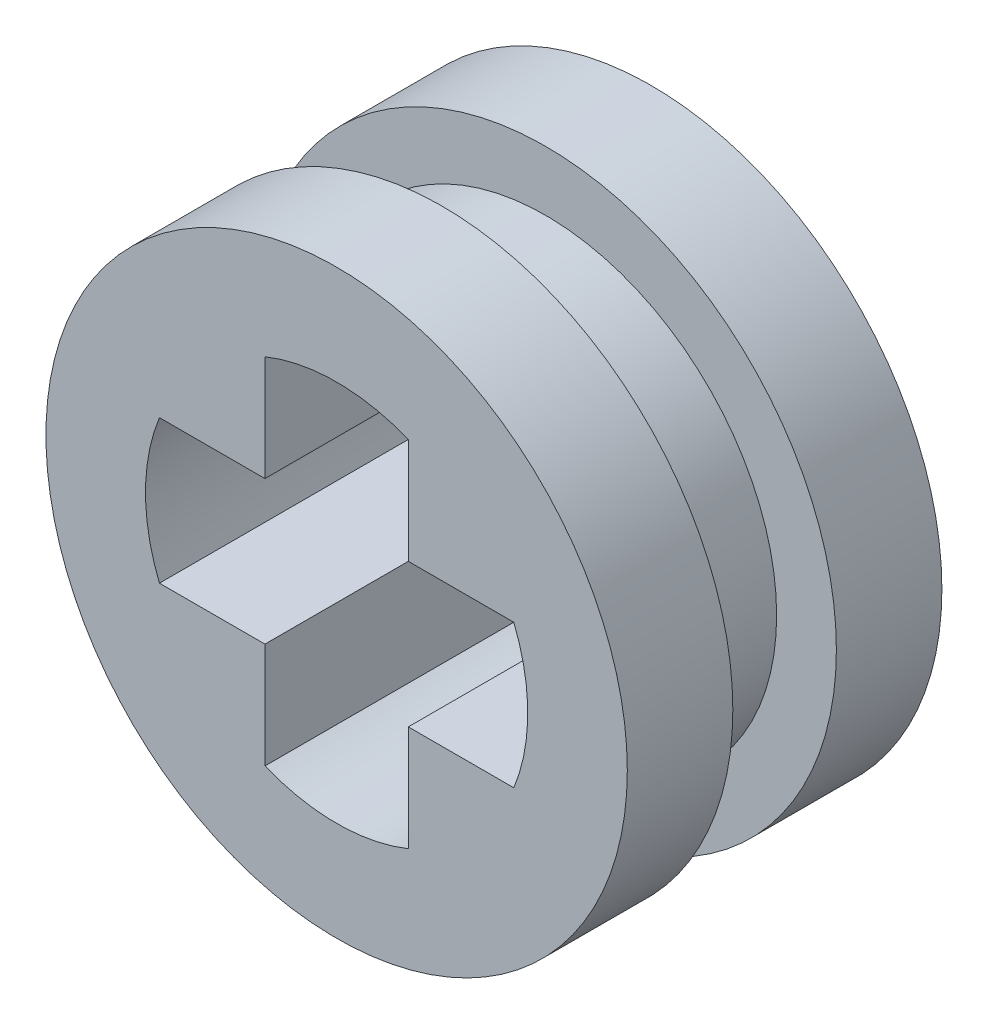
SolidWorks part; units mm, degrees
ref_plane "Front Plane" through (0, 0, 0) normal (0, 0, 1) x (1, 0, 0)
ref_plane "Top Plane" through (0, 0, 0) normal (0, 1, 0) x (1, 0, 0)
ref_plane "Right Plane" through (0, 0, 0) normal (1, 0, 0) x (0, 0, -1)
sketch "Sketch1" plane through (0, 0, 0) normal (0, 0, 1) x (1, 0, 0)
  line L1 (0.9, -2.4) -> (-0.9, -2.4)
  line L2 (0.9, -2.4) -> (0.9, 2.4)
  line L3 (0.9, 2.4) -> (-0.9, 2.4)
  line L4 (-0.9, -2.4) -> (-0.9, 2.4)
  line L5 (0.9, -2.4) -> (-0.9, 2.4) construction
  line L6 (0.9, 2.4) -> (-0.9, -2.4) construction
  line L7 (-2.4, -0.9) -> (2.4, -0.9)
  line L8 (-2.4, -0.9) -> (-2.4, 0.9)
  line L9 (-2.4, 0.9) -> (2.4, 0.9)
  line L10 (2.4, -0.9) -> (2.4, 0.9)
  line L11 (-2.4, -0.9) -> (2.4, 0.9) construction
  line L12 (-2.4, 0.9) -> (2.4, -0.9) construction
  circle A0 centre (0, 0) radius 2.4
  circle A1 centre (0, 0) radius 3.65
  dimension "D1" = 4.8
  dimension "D2" = 7.3
  dimension "D3" = 1.8
extrude "Boss-Extrude1" add sketch "Sketch1" along normal mid plane 3.95 contours A1 A0 L9 L10 L7 L2 L1 L4 L8 L3 | L4 A0 L9 | A0 L3 L4 | A0 L2 L3 | L9 A0 L2 | A0 L10 L9 | A0 L7 L10 | L2 A0 L7 | L7 A0 L4 | A0 L1 L2 | A0 L4 L1 | A0 L8 L7 | A0 L9 L8
sketch "Sketch2" plane through (0, 0, 0) normal (0, 0, 1) x (1, 0, 0)
  circle A0 centre (0, 0) radius 2.9
  dimension "D1" = 5.8
extrude "Cut-Extrude1" cut sketch "Sketch2" against normal mid plane 1.3 flip side to cut
